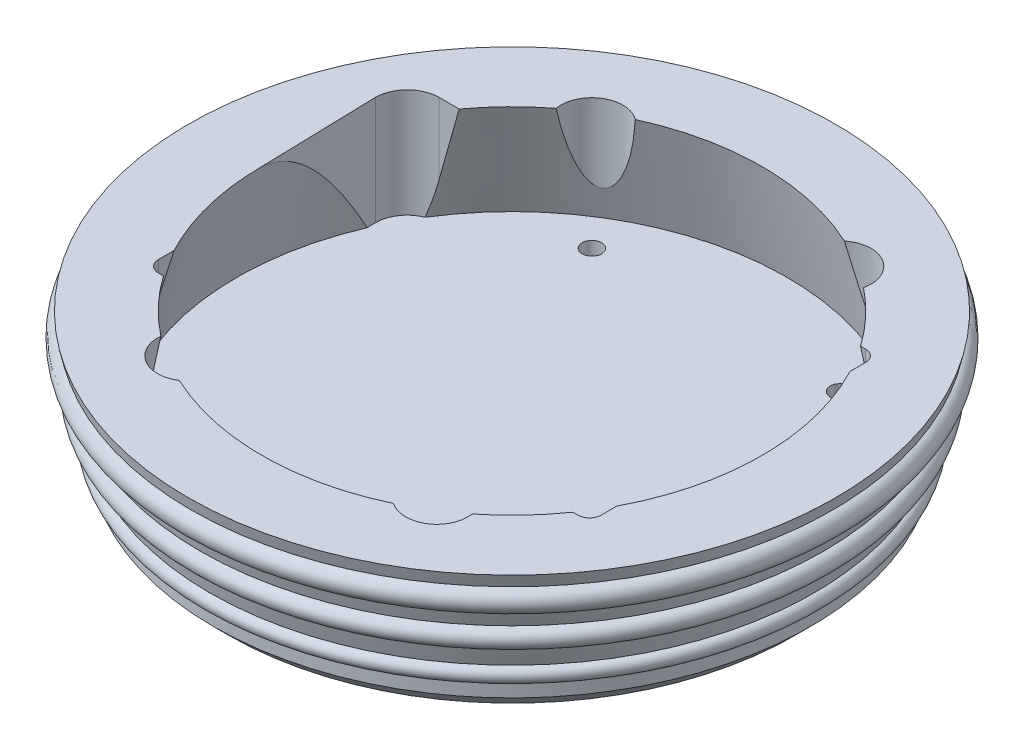
SolidWorks part; units mm, degrees
ref_plane "Front Plane" through (0, 0, 0) normal (0, 0, 1) x (1, 0, 0)
ref_plane "Top Plane" through (0, 0, 0) normal (0, 1, 0) x (1, 0, 0)
ref_plane "Right Plane" through (0, 0, 0) normal (1, 0, 0) x (0, 0, -1)
sketch "Sketch1" plane through (0, 0, 0) normal (0, 1, 0) x (1, 0, 0)
  circle A0 centre (0, 0) radius 38.5
  dimension "D1" = 77
extrude "Boss-Extrude1" add sketch "Sketch1" along normal blind 4
sketch "Sketch2" plane through (0, 4, 0) normal (0, 1, 0) x (1, 0, 0)
  circle A0 centre (0, 0) radius 38.5
  circle A1 centre (0, 0) radius 38.5 construction
  circle A2 centre (0, 0) radius 35.5
  circle A3 centre (0, 0) radius 35.5
  dimension "D1" = 3
extrude "Boss-Extrude2" add sketch "Sketch2" along normal blind 14 draft 13 draft outward yes
sketch "Sketch3" plane through (0, 18, 0) normal (0, 1, 0) x (1, 0, 0)
  line L0 (18.55, -28.55) -> (18.55, -18.55)
  line L1 (28.55, -18.55) -> (-28.55, -18.55) construction
  line L2 (28.55, -18.55) -> (28.55, 18.55)
  line L3 (28.55, 18.55) -> (-28.55, 18.55) construction
  line L4 (-28.55, -18.55) -> (-28.55, 18.55)
  line L5 (28.55, -18.55) -> (-28.55, 18.55) construction
  line L6 (28.55, 18.55) -> (-28.55, -18.55) construction
  line L7 (-18.55, -28.55) -> (18.55, -28.55)
  line L8 (-18.55, -28.55) -> (-18.55, 28.55) construction
  line L9 (-18.55, 28.55) -> (18.55, 28.55)
  line L10 (18.55, -28.55) -> (18.55, 28.55) construction
  line L11 (-18.55, -28.55) -> (18.55, 28.55) construction
  line L12 (-18.55, 28.55) -> (18.55, -28.55) construction
  line L13 (18.55, -18.55) -> (28.55, -18.55)
  line L14 (18.55, 28.55) -> (18.55, 18.55)
  line L15 (18.55, 18.55) -> (28.55, 18.55)
  line L16 (-18.55, 28.55) -> (-18.55, 18.55)
  line L17 (-18.55, 18.55) -> (-28.55, 18.55)
  line L18 (-18.55, -28.55) -> (-18.55, -18.55)
  line L19 (-18.55, -18.55) -> (-28.55, -18.55)
  point P0 (0, 0)
  point P6 (0, 0)
  dimension "D1" = 37.1
  dimension "D2" = 57.1
extrude "Cut-Extrude1" cut sketch "Sketch3" against normal up to surface (14 mm away) up to face at (0, 4, 35.5)
fillet "Fillet2" radius 1.5 4 edges at (-28.55, 14.1466, 18.55) (-28.55, 14.1466, -18.55) (28.55, 14.1466, -18.55) (28.55, 14.1466, 18.55)
sketch "Sketch7" plane through (0, 4, 0) normal (0, 1, 0) x (1, 0, 0)
  circle A0 centre (16.15, 26.15) radius 1.25
  circle A1 centre (16.15, -25.85) radius 1.25
  circle A2 centre (-15.85, -25.85) radius 1.25
  circle A3 centre (-15.85, 26.15) radius 1.25
  circle A4 centre (-15.85, 26.15) radius 1.6 construction
  circle A5 centre (16.15, 26.15) radius 1.6 construction
  circle A6 centre (16.15, -25.85) radius 1.6 construction
  circle A7 centre (-15.85, -25.85) radius 1.6 construction
  dimension "D1" = 2.5
extrude "Cut-Extrude4" cut sketch "Sketch7" against normal up to surface (4 mm away) up to face at (0, 0, 38.5)
sketch "Sketch8" plane through (0, 4, 0) normal (0, 1, 0) x (1, 0, 0)
  circle A0 centre (-15.85, -25.85) radius 4
  circle A1 centre (-15.85, 26.15) radius 4
  circle A2 centre (16.15, -25.85) radius 4
  circle A3 centre (16.15, 26.15) radius 4
  dimension "D1" = 8
extrude "Cut-Extrude5" cut sketch "Sketch8" along normal up to surface (14 mm away) up to face at (0, 18, 0)
ref_plane "Plane1" through (0, 10, 0) normal (0, -1, 0) x (-1, 0, 0)
ref_plane "Plane2" through (0, 15, 0) normal (0, -1, 0) x (-1, 0, 0)
ref_plane "Plane3" through (0, 5, 0) normal (0, -1, 0) x (-1, 0, 0)
sketch "Sketch11" plane through (0, 15, 0) normal (0, -1, 0) x (-1, 0, 0)
  circle A0 centre (0, 0) radius 41
  dimension "D1" = 82
sketch "Sketch12" plane through (0, 5, 0) normal (0, -1, 0) x (-1, 0, 0)
  circle A0 centre (0, 0) radius 38.75
  dimension "D1" = 77.5
sketch "Sketch13" plane through (0, 0, 0) normal (1, 0, 0) x (0, 0, -1)
  circle A0 centre (41, 15) radius 1.5
  dimension "D1" = 3
sketch "Sketch14" plane through (0, 0, 0) normal (1, 0, 0) x (0, 0, -1)
  circle A0 centre (38.75, 5) radius 1
  dimension "D1" = 2
sketch "Sketch10" plane through (0, 0, 0) normal (1, 0, 0) x (0, 0, -1)
  circle A0 centre (40, 10) radius 1.25
  dimension "D1" = 2.5
sketch "Sketch9" plane through (0, 10, 0) normal (0, -1, 0) x (-1, 0, 0)
  circle A0 centre (0, 0) radius 40
  dimension "D1" = 80
sweep "Sweep1" add profiles "Sketch10" path "Sketch9"
sweep "Sweep2" add profiles "Sketch13" path "Sketch11"
sweep "Sweep3" add profiles "Sketch14" path "Sketch12"
chamfer "Chamfer1" distance 2 angle 45 1 edges at (0, 0, 38.5)
sketch "Sketch15" plane through (0, 18, 0) normal (0, 1, 0) x (1, 0, 0)
  line L0 (-32.6672, 15.037) -> (-32.2678, 0)
  line L1 (-28.55, 19.1542) -> (-25.9679, 19.1542)
  circle A0 centre (-28.55, 15.037) radius 4.1172
  arc A2 (-28.55, 15.037) -> (-28.55, -15.037) centre (0, 0) ccw construction
  arc A3 (-19.7941, 25.4835) -> (-26.4029, 18.55) centre (0, 0) ccw construction
  arc M21 (-28.55, -15.037) -> (-28.55, 15.037) centre (0, 0) cw
  line M22 (-28.55, 15.037) -> (-28.55, 17.05)
  arc M23 (-28.55, 17.05) -> (-27.05, 18.55) centre (-27.05, 17.05) cw
  line M24 (-27.05, 18.55) -> (-26.4029, 18.55)
  arc M25 (-26.4029, 18.55) -> (-19.7941, 25.4835) centre (0, 0) cw
extrude "Cut-Extrude7" cut sketch "Sketch15" against normal up to surface (14 mm away) contours A0 L0 M24 M21 M22 M23 | A0 L0 M21 | A0 L1 M25 up to face at (16.15, 4, -24.9)
